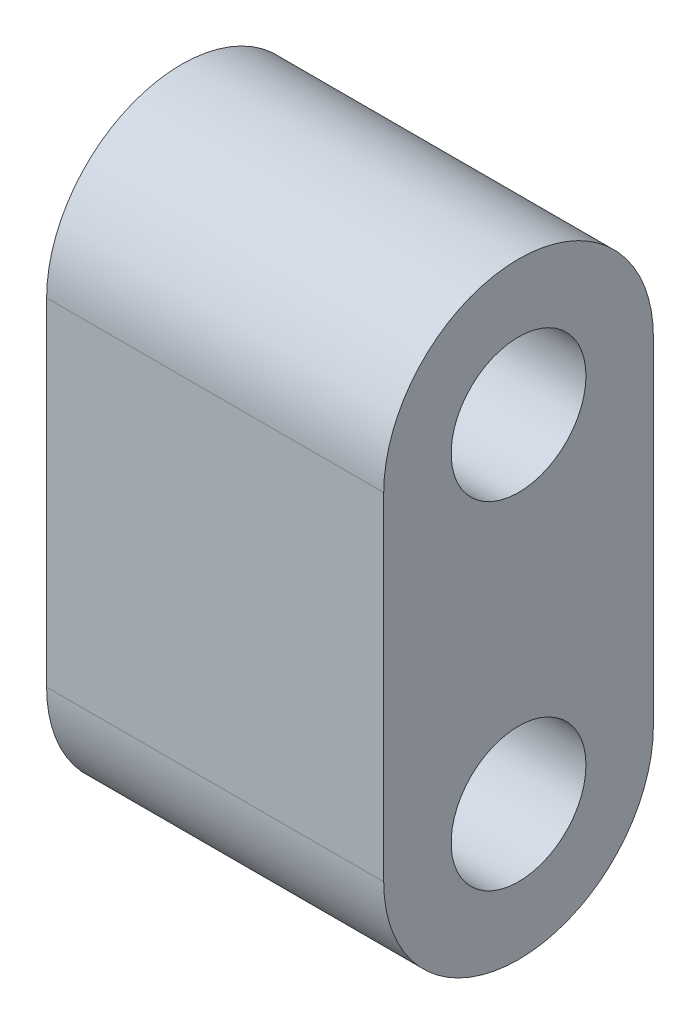
SolidWorks part; units mm, degrees
material "Plain Carbon Steel"
ref_plane "Front Plane" through (0, 0, 0) normal (0, 0, 1) x (1, 0, 0)
ref_plane "Top Plane" through (0, 0, 0) normal (0, 1, 0) x (1, 0, 0)
ref_plane "Right Plane" through (0, 0, 0) normal (1, 0, 0) x (0, 0, -1)
sketch "Sketch1" plane through (0, 0, 0) normal (1, 0, 0) x (0, 0, -1)
  line L0 (0, 0) -> (0, 6.5747) construction
  line L1 (4, 10) -> (4, 0)
  line L2 (-4, 10) -> (-4, 0)
  circle A0 centre (0, 0) radius 2
  circle A1 centre (0, 10) radius 2
  arc A2 (4, 10) -> (-4, 10) centre (0, 10) ccw
  arc A3 (4, 0) -> (-4, 0) centre (0, 0) cw
  dimension "D1" = 4
  dimension "D2" = 4
  dimension "D5" = 4
  dimension "D3" = 10
  dimension "D4" = 8
extrude "Boss-Extrude1" add sketch "Sketch1" along normal mid plane 10
